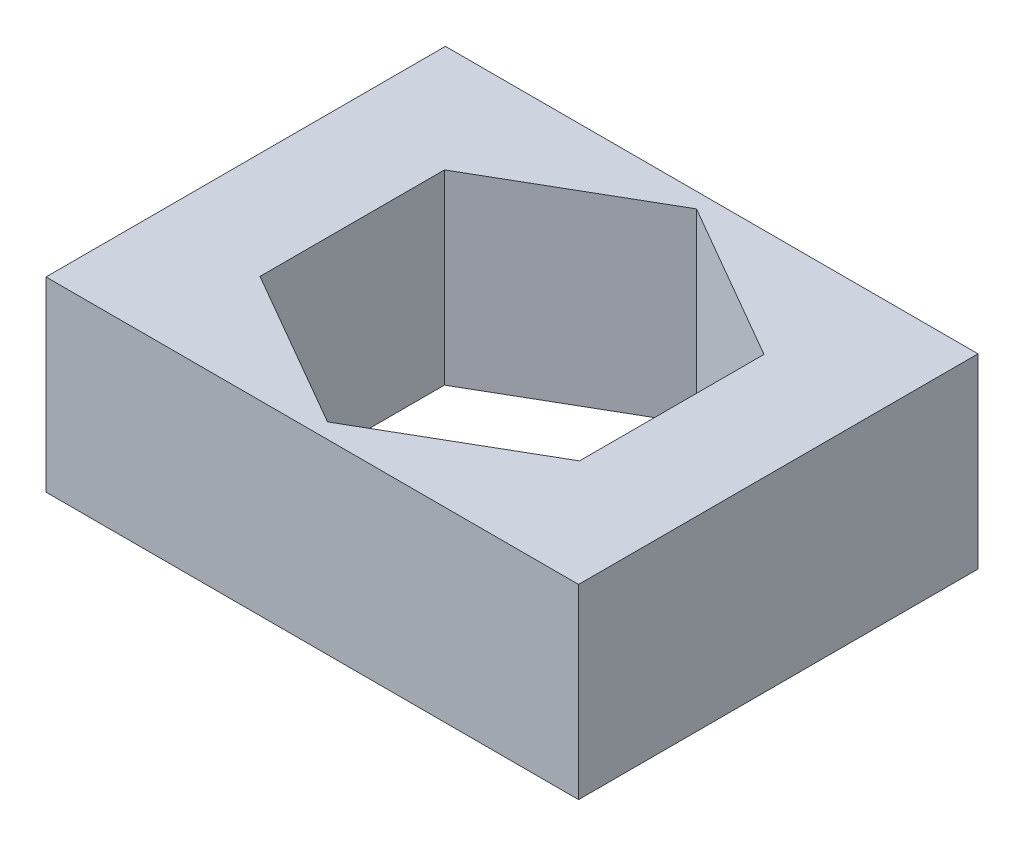
SolidWorks part; units mm, degrees
ref_plane "Alzado" through (0, 0, 0) normal (0, 0, 1) x (1, 0, 0)
ref_plane "Planta" through (0, 0, 0) normal (0, 1, 0) x (1, 0, 0)
ref_plane "Vista lateral" through (0, 0, 0) normal (1, 0, 0) x (0, 0, -1)
sketch "Croquis1" plane through (0, 0, 0) normal (0, 1, 0) x (1, 0, 0)
  line L0 (0, 91.6054) -> (0, -80.3116) construction
  line L1 (-92.0237, 0) -> (101.2261, 0) construction
  line L3 (-10, -7.5) -> (10, -7.5)
  line L4 (-10, -7.5) -> (-10, 7.5)
  line L5 (-10, 7.5) -> (10, 7.5)
  line L6 (10, -7.5) -> (10, 7.5)
  line L7 (-10, -7.5) -> (10, 7.5) construction
  line L8 (-10, 7.5) -> (10, -7.5) construction
  point P5 (0, 0)
  dimension "D1" = 15
  dimension "D2" = 20
extrude "Saliente-Extruir1" add sketch "Croquis1" along normal blind 7
sketch "Croquis8" plane through (0, 0, 0) normal (0, -1, 0) x (1, 0, 0)
  line L0 (0, 8.2472) -> (0, -8.5558) construction
  line L1 (-11.2515, 0) -> (11.0607, 0) construction
  line L3 (0, 6.9282) -> (-6, 3.4641)
  line L4 (-6, 3.4641) -> (-6, -3.4641)
  line L5 (-6, -3.4641) -> (0, -6.9282)
  line L6 (0, -6.9282) -> (6, -3.4641)
  line L7 (6, -3.4641) -> (6, 3.4641)
  line L8 (6, 3.4641) -> (0, 6.9282)
  circle A0 centre (0, 0) radius 6 construction
  dimension "D1" = 12
extrude "Cortar-Extruir4" cut sketch "Croquis8" against normal blind 7
sketch "Croquis9" plane through (0, 0, 0) normal (0, -1, 0) x (1, 0, 0)
  line L0 (0, -7.053) -> (0, 8.4836) construction
  line L1 (10.9122, 0) -> (-12.1099, 0) construction
  line L3 (7.5853, 6.3211) -> (-7.5853, 6.3211)
  line L4 (7.5853, 6.3211) -> (7.5853, -6.3211)
  line L5 (7.5853, -6.3211) -> (-7.5853, -6.3211)
  line L6 (-7.5853, 6.3211) -> (-7.5853, -6.3211)
  line L7 (7.5853, 6.3211) -> (-7.5853, -6.3211) construction
  line L8 (7.5853, -6.3211) -> (-7.5853, 6.3211) construction
  point P5 (0, 0)
  dimension "D1" = 12.6422
  dimension "D2" = 15.1706
